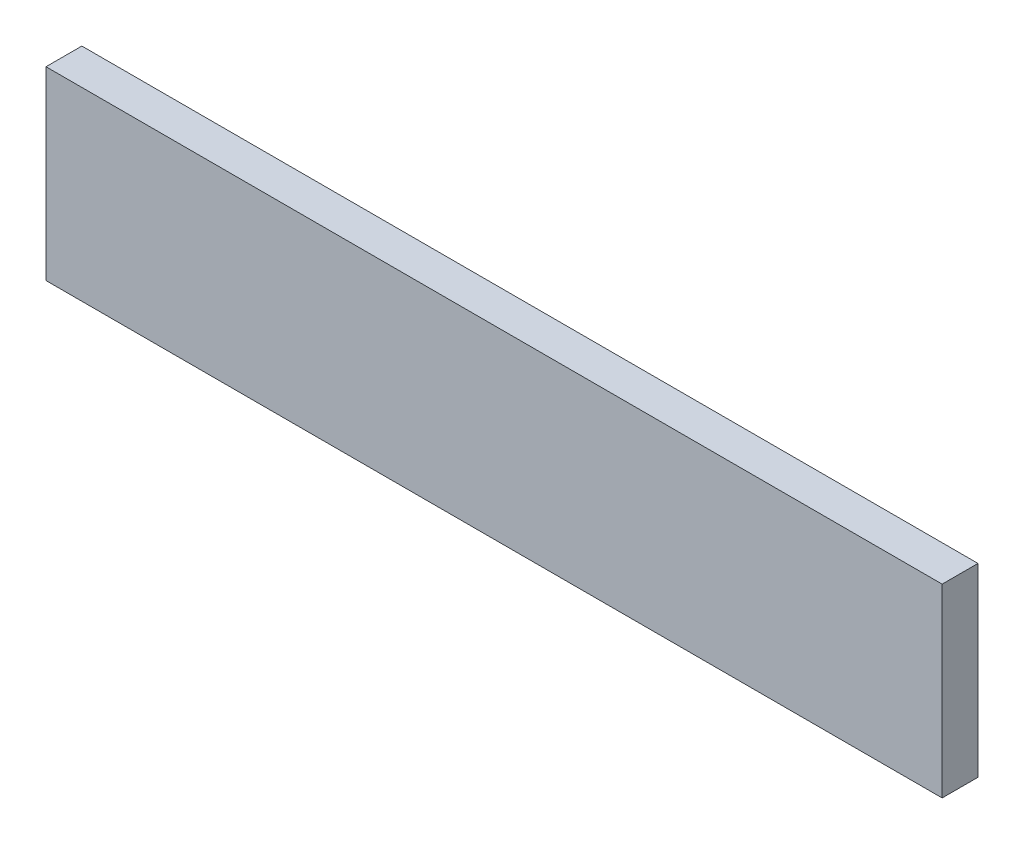
SolidWorks part; units mm, degrees
material "Acrylic (Medium-high impact)"
ref_plane "Front Plane" through (0, 0, 0) normal (0, 0, 1) x (1, 0, 0)
ref_plane "Top Plane" through (0, 0, 0) normal (0, 1, 0) x (1, 0, 0)
ref_plane "Right Plane" through (0, 0, 0) normal (1, 0, 0) x (0, 0, -1)
sketch "Sketch1" plane through (0, 0, 0) normal (0, 0, 1) x (1, 0, 0)
  line L1 (-1007.4157, 60.1348) -> (-857.4157, 60.1348)
  line L2 (-1007.4157, 60.1348) -> (-1007.4157, 29.1348)
  line L3 (-1007.4157, 29.1348) -> (-857.4157, 29.1348)
  line L7 (-857.4157, 60.1348) -> (-857.4157, 29.1348)
  dimension "D1" = 31
  dimension "D2" = 150
extrude "Boss-Extrude1" add sketch "Sketch1" along normal blind 6
